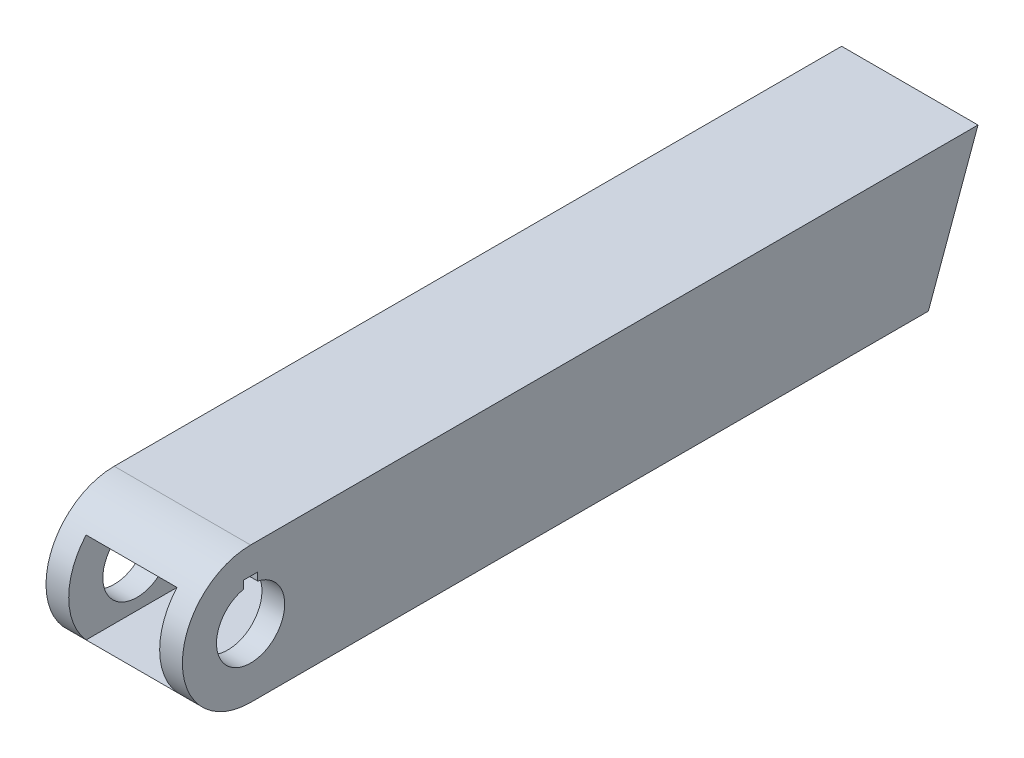
SolidWorks part; units mm, degrees
material "6061 Alloy"
ref_plane "Front Plane" through (0, 0, 0) normal (0, 0, 1) x (1, 0, 0)
ref_plane "Top Plane" through (0, 0, 0) normal (0, 1, 0) x (1, 0, 0)
ref_plane "Right Plane" through (0, 0, 0) normal (1, 0, 0) x (0, 0, -1)
sketch "Sketch1" plane through (0, 0, 0) normal (1, 0, 0) x (0, 0, -1)
  line L0 (-12.7, 22.225) -> (81.9664, 22.225) construction
  line L1 (88.9, 22.225) -> (81.9664, 22.225) construction
  line L4 (366.1698, -210.432) -> (353.9247, -225.0251) construction
  line L6 (-12.7, 3.175) -> (81.9664, 3.175) construction
  line L7 (-12.7, 22.225) -> (-25.4, 22.225) construction
  line L8 (-25.4, 22.225) -> (-25.4, 3.175) construction
  line L9 (-12.7, 3.175) -> (-25.4, 3.175) construction
  line L10 (-12.7, 22.225) -> (-12.7, 3.175) construction
  line L11 (-12.7, 22.225) -> (81.9664, 22.225)
  line L12 (88.9, 22.225) -> (81.9664, 22.225)
  line L13 (88.9, 22.225) -> (81.9664, 3.175)
  line L15 (366.1698, -210.432) -> (353.9247, -225.0251)
  line L17 (-12.7, 3.175) -> (81.9664, 3.175)
  line L18 (-12.7, 22.225) -> (-25.4, 22.225)
  line L19 (-25.4, 22.225) -> (-25.4, 3.175)
  line L20 (-12.7, 3.175) -> (-25.4, 3.175)
  line L21 (-12.7, 22.225) -> (-12.7, 3.175)
extrude "Boss-Extrude1" add sketch "Sketch1" along normal blind 19.05 contours L11 L21 L17 L13 L12
sketch "Sketch2" plane through (0, 0, 12.7) normal (0, 0, 1) x (1, 0, 0)
  line L0 (19.05, 22.225) -> (0, 22.225) construction
  line L1 (15.875, 6.35) -> (3.175, 6.35)
  line L2 (15.875, 6.35) -> (15.875, 19.05)
  line L3 (15.875, 19.05) -> (3.175, 19.05)
  line L4 (3.175, 6.35) -> (3.175, 19.05)
  line L5 (15.875, 6.35) -> (3.175, 19.05) construction
  line L6 (15.875, 19.05) -> (3.175, 6.35) construction
  line L7 (19.05, 3.175) -> (0, 3.175) construction
  line L8 (19.05, 22.225) -> (19.05, 3.175) construction
  line L9 (0, 22.225) -> (0, 3.175) construction
  point P0 (9.525, 12.7)
  dimension "D1" = 3.175
  dimension "D2" = 3.175
  dimension "D3" = 3.175
  dimension "D4" = 3.175
extrude "Cut-Extrude3" cut sketch "Sketch2" against normal through all
sketch "Sketch3" plane through (0, 0, 12.7) normal (0, 0, 1) x (1, 0, 0)
  line L0 (15.875, 19.05) -> (3.175, 19.05) construction
  line L1 (3.175, 19.05) -> (3.175, 6.35) construction
  line L2 (3.175, 6.35) -> (15.875, 6.35) construction
  line L3 (15.875, 6.35) -> (15.875, 19.05) construction
  line L4 (0, 22.225) -> (0, 3.175)
  line L5 (0, 3.175) -> (19.05, 3.175)
  line L6 (19.05, 3.175) -> (19.05, 22.225)
  line L7 (19.05, 22.225) -> (0, 22.225)
  line L8 (0, 22.225) -> (0, 3.175)
  line L9 (0, 3.175) -> (19.05, 3.175)
  line L10 (19.05, 3.175) -> (19.05, 22.225)
  line L11 (19.05, 22.225) -> (0, 22.225)
  line L12 (15.875, 19.05) -> (3.175, 19.05)
  line L13 (3.175, 19.05) -> (3.175, 6.35)
  line L14 (3.175, 6.35) -> (15.875, 6.35)
  line L15 (15.875, 6.35) -> (15.875, 19.05)
  dimension "D1" = 0
extrude "Boss-Extrude2" add sketch "Sketch3" along normal blind 12.7
sketch "Sketch4" plane through (19.05, 0, 0) normal (1, 0, 0) x (0, 0, -1)
  line L0 (-25.4, 3.175) -> (81.9664, 3.175) construction
  line L1 (-25.4, 22.225) -> (88.9, 22.225) construction
  line L2 (-25.4, 3.175) -> (-25.4, 22.225) construction
  line L4 (-11.7, 16.4625) -> (-13.7, 16.4625)
  line L5 (-11.7, 16.4625) -> (-11.7, 18.4625)
  line L6 (-11.7, 18.4625) -> (-13.7, 18.4625)
  line L7 (-13.7, 16.4625) -> (-13.7, 18.4625)
  line L8 (-11.7, 16.4625) -> (-13.7, 18.4625) construction
  line L9 (-11.7, 18.4625) -> (-13.7, 16.4625) construction
  arc A0 (-12.7, 3.175) -> (-12.7, 22.225) centre (-12.7, 12.7) cw
  arc A1 (-12.7, 22.225) -> (-12.7, 3.175) centre (-12.7, 12.7) cw construction
  circle A2 centre (-12.7, 12.7) radius 4.7625
  point P10 (-12.7, 17.4625)
  line M1 (88.9, 22.225) -> (-25.4, 22.225)
  line M2 (-25.4, 22.225) -> (-25.4, 3.175)
  line M3 (-25.4, 3.175) -> (81.9664, 3.175)
  dimension "D1" = 12.7
  dimension "D2" = 9.525
  dimension "D3" = 9.525
  dimension "D4" = 2
  dimension "D5" = 2
extrude "Cut-Extrude5" cut sketch "Sketch4" against normal blind 19.05 contours L7 A2 L5 L4 | A2 L5 L6 L7 | L5 A2 L7 L4 | A0 M3 M1 M2
